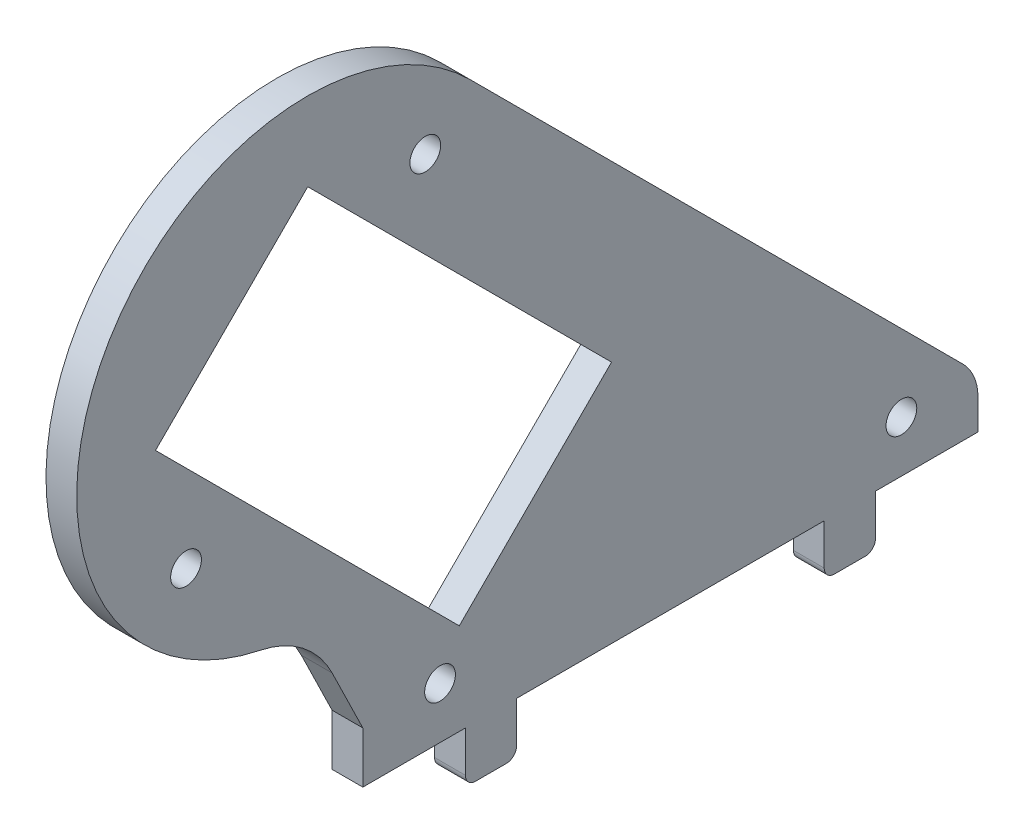
SolidWorks part; units mm, degrees
ref_plane "Front Plane" through (0, 0, 0) normal (0, 0, 1) x (1, 0, 0)
ref_plane "Top Plane" through (0, 0, 0) normal (0, 1, 0) x (1, 0, 0)
ref_plane "Right Plane" through (0, 0, 0) normal (1, 0, 0) x (0, 0, -1)
sketch "Sketch3" plane through (0, 0, 0) normal (1, 0, 0) x (0, 0, -1)
  line L0 (0, 21.1957) -> (0, -21.1957) construction
  line L1 (20, -2.5) -> (15, -2.5)
  line L2 (20, -2.5) -> (20, 2.5)
  line L3 (30, 7.5) -> (-19.4975, 56.9975)
  line L4 (-20, -2.5) -> (-20, 2.5)
  line L5 (20, -2.5) -> (-20, 2.5) construction
  line L6 (20, 2.5) -> (-20, -2.5) construction
  line L7 (-20, 2.5) -> (-30, 2.5)
  line L8 (30, 7.5) -> (-30, 7.5)
  line L9 (30, 7.5) -> (30, 2.5)
  line L10 (30, 2.5) -> (20, 2.5)
  line L11 (-30, 7.5) -> (-30, 2.5)
  line L12 (30, 7.5) -> (-30, 2.5) construction
  line L13 (30, 2.5) -> (-30, 7.5) construction
  line L14 (-35.4074, 18.5876) -> (-30, 7.5)
  line L15 (-15, -2.5) -> (-20, -2.5)
  line L16 (15, 2.5) -> (-15, 2.5)
  line L17 (15, 2.5) -> (15, -2.5)
  line L19 (-15, 2.5) -> (-15, -2.5)
  line L20 (15, 2.5) -> (-15, -2.5) construction
  line L21 (15, -2.5) -> (-15, 2.5) construction
  circle A0 centre (-35.4074, 41.0876) radius 22.5
  point P0 (0, 0)
  point P8 (0, 5)
  point P17 (0, 0)
  dimension "D7" = 45
  dimension "D1" = 5
  dimension "D2" = 40
  dimension "D3" = 5
  dimension "D4" = 60
  dimension "D5" = 45
  dimension "D6" = 70
  dimension "D8" = 5
  dimension "D9" = 30
extrude "Boss-Extrude1" add sketch "Sketch3" along normal blind 3 contours A0 L14 L8 L3 | A0 | L8 L11 L7 L4 L1 L2 L10 L9
sketch "Sketch4" plane through (0, 0, 0) normal (-1, 0, 0) x (0, 0, 1)
  line L0 (1.1127, 21.6421) -> (40.0036, 60.533)
  line L1 (40.0036, 60.533) -> (54.8528, 45.6838)
  line L2 (54.8528, 45.6838) -> (15.9619, 6.7929)
  line L3 (15.9619, 6.7929) -> (1.1127, 21.6421)
  line L4 (-30, 7.5) -> (19.4975, 56.9975) construction
  line L5 (20.5581, 41.0876) -> (35.4074, 26.2383) construction
  line L8 (35.4074, 41.0876) -> (8.5373, 14.2175) construction
  line L9 (5.7442, 26.2737) -> (20.5935, 11.4244)
  line L10 (35.372, 55.9015) -> (50.2213, 41.0522)
  dimension "D1" = 21
  dimension "D2" = 55
  dimension "D3" = 17
  dimension "D4" = 41.9
extrude "Cut-Extrude2" cut sketch "Sketch4" against normal blind 10 contours L10 L0 L9 L2
sketch "Sketch5" plane through (0, 0, 0) normal (-1, 0, 0) x (0, 0, 1)
  line L0 (23.9104, 52.9251) -> (68.5807, 8.2548) construction
  line L1 (20.5581, 41.0876) -> (35.4074, 26.2383) construction
  line L2 (20, -2.5) -> (20, 2.5) construction
  line L3 (-20, -2.5) -> (-15, -2.5) construction
  line L5 (1.1127, 21.6421) -> (40.0036, 60.533) construction
  line L6 (54.8528, 45.6838) -> (15.9619, 6.7929) construction
  line L7 (-30, 2.5) -> (-20, 2.5) construction
  line L8 (20, 2.5) -> (30, 2.5) construction
  circle A0 centre (22.4713, 7.5) radius 1.5
  circle A1 centre (-22.5287, 7.5) radius 1.5
  circle A2 centre (23.9104, 52.9251) radius 1.5
  circle A3 centre (47.2449, 29.5906) radius 1.5
  point P18 (0, 0)
  dimension "D1" = 3
  dimension "D2" = 3
  dimension "D3" = 3
  dimension "D4" = 3
  dimension "D5" = 6
  dimension "D6" = 6
  dimension "D7" = 5
  dimension "D8" = 5
  dimension "D9" = 45
extrude "Cut-Extrude3" cut sketch "Sketch5" against normal blind 10
fillet "Fillet1" radius 10 1 edges at (1.5, 18.5876, 35.4074)
fillet "Fillet2" radius 1 4 edges at (1.5, -2.5, 20) (1.5, -2.5, 15) (1.5, -2.5, -15) (1.5, -2.5, -20)
fillet "Fillet3" radius 5 1 edges at (1.5, 7.5, -30)
